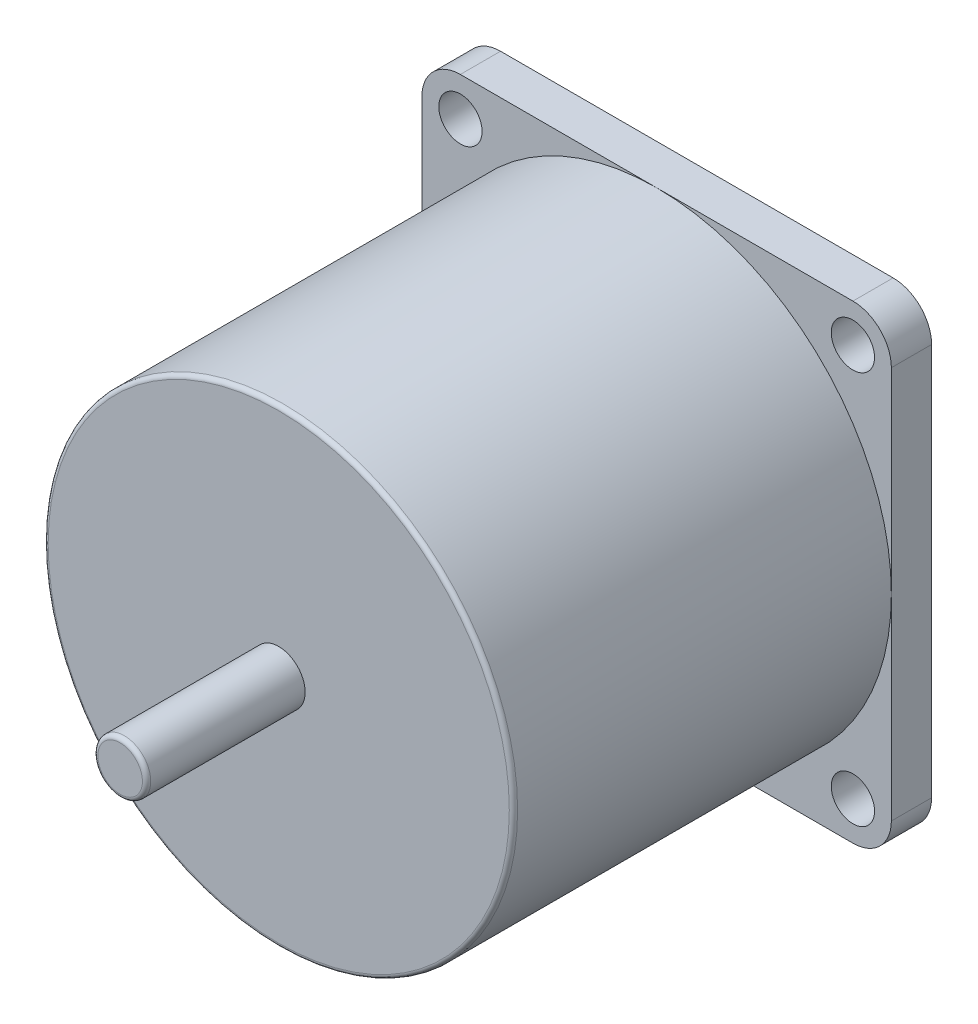
SolidWorks part; units mm, degrees
ref_plane "Plano frontal" through (0, 0, 0) normal (0, 0, 1) x (1, 0, 0)
ref_plane "Plano superior" through (0, 0, 0) normal (0, 1, 0) x (1, 0, 0)
ref_plane "Plano direito" through (0, 0, 0) normal (1, 0, 0) x (0, 0, -1)
sketch "Esboço1" plane through (0, 0, 0) normal (0, 0, 1) x (1, 0, 0)
  line L1 (-23.58, -28.2) -> (23.58, -28.2)
  line L2 (-28.2, -23.58) -> (-28.2, 23.58)
  line L3 (-23.58, 28.2) -> (23.58, 28.2)
  line L4 (28.2, -23.58) -> (28.2, 23.58)
  arc A0 (-23.58, 28.2) -> (-28.2, 23.58) centre (-23.58, 23.58) ccw
  arc A1 (-28.2, -23.58) -> (-23.58, -28.2) centre (-23.58, -23.58) ccw
  arc A2 (23.58, -28.2) -> (28.2, -23.58) centre (23.58, -23.58) ccw
  arc A3 (28.2, 23.58) -> (23.58, 28.2) centre (23.58, 23.58) ccw
  circle A4 centre (-23.57, 23.57) radius 2.6
  circle A5 centre (23.5755, 23.6293) radius 2.6
  circle A6 centre (23.58, -23.58) radius 2.6
  circle A7 centre (-23.58, -23.58) radius 2.6
  circle A8 centre (0, 0) radius 3.175
  point P0 (0, 0)
  point P6 (0, 0)
  point P7 (0, 0)
  point P14 (-28.2, 28.2)
  point P19 (28.2, -28.2)
  point P22 (28.2, 28.2)
  dimension "D5" = 4.62
  dimension "D6" = 5.2
  dimension "D3" = 6.35
  dimension "D1" = 56.4
  dimension "D2" = 56.4
extrude "Ressalto-extrusão1" add sketch "Esboço1" along normal blind 4.83
sketch "Esboço2" plane through (0, 0, 0) normal (0, 0, 1) x (1, 0, 0)
  circle A0 centre (0, 0) radius 19.05
  circle A1 centre (0, 0) radius 3.175
  dimension "D1" = 38.1
extrude "Ressalto-extrusão2" add sketch "Esboço2" against normal blind 1.52
sketch "Esboço3" plane through (0, 0, 4.83) normal (0, 0, 1) x (1, 0, 0)
  circle A0 centre (0, 0) radius 28.2
extrude "Ressalto-extrusão3" add sketch "Esboço3" along normal blind 45.4
sketch "Esboço4" plane through (0, 0, 4.83) normal (0, 0, -1) x (-1, 0, 0)
  circle A0 centre (0, 0) radius 3.175
extrude "Ressalto-extrusão4" add sketch "Esboço4" along normal blind 20.6
fillet "Filete1" radius 0.5 1 edges at (-3.175, 0, -15.77)
sketch "Esboço5" plane through (0, 0, 50.23) normal (0, 0, 1) x (1, 0, 0)
  circle A0 centre (0, 0) radius 3.175
  dimension "D1" = 6.35
extrude "Ressalto-extrusão5" add sketch "Esboço5" along normal blind 19.05
fillet "Filete2" radius 0.5 1 edges at (3.175, 0, 69.28)
fillet "Filete3" radius 0.5 1 edges at (28.2, 0, 50.23)
